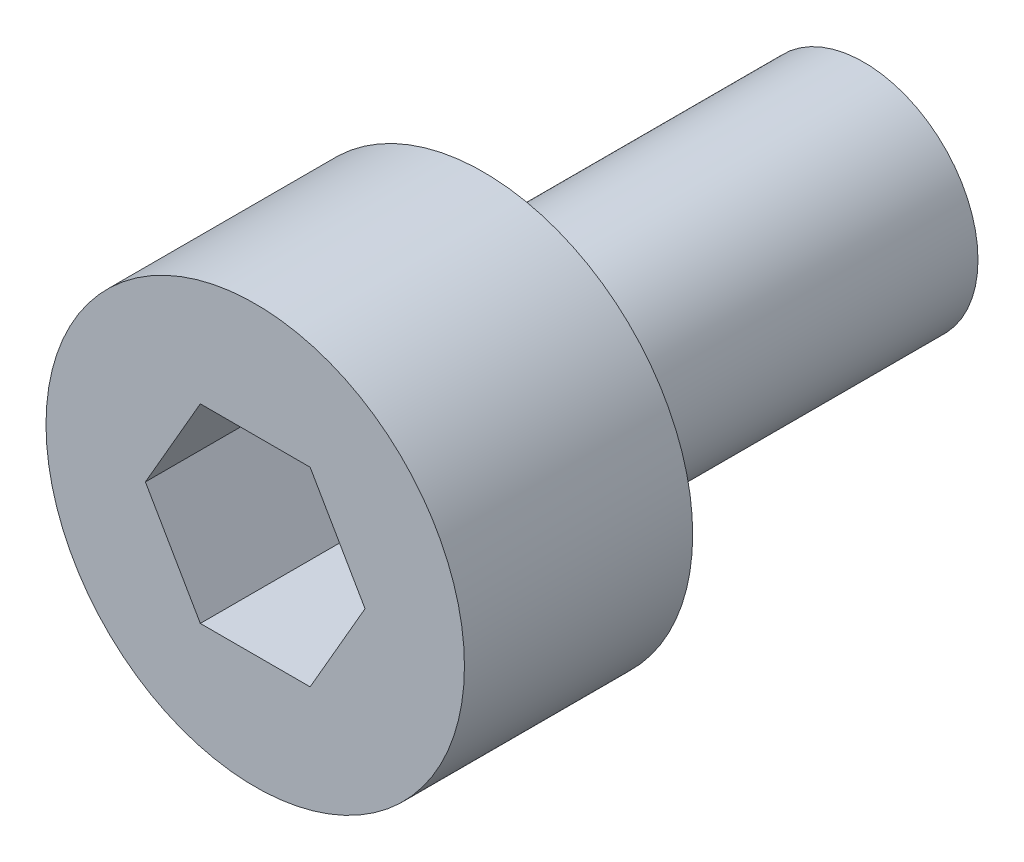
SolidWorks part; units mm, degrees
ref_plane "Plan de face" through (0, 0, 0) normal (0, 0, 1) x (1, 0, 0)
ref_plane "Plan de dessus" through (0, 0, 0) normal (0, 1, 0) x (1, 0, 0)
ref_plane "Plan de droite" through (0, 0, 0) normal (1, 0, 0) x (0, 0, -1)
sketch "Esquisse1" plane through (0, 0, 0) normal (0, 0, 1) x (1, 0, 0)
  circle A0 centre (0, 0) radius 1.5
  dimension "D1" = 3
extrude "Boss.-Extru.1" add sketch "Esquisse1" along normal blind 5
sketch "Esquisse2" plane through (0, 0, 5) normal (0, 0, 1) x (1, 0, 0)
  circle A0 centre (0, 0) radius 2.75
  dimension "D1" = 5.5
extrude "Boss.-Extru.2" add sketch "Esquisse2" along normal blind 3
sketch "Esquisse3" plane through (0, 0, 8) normal (0, 0, 1) x (1, 0, 0)
  line L1 (1.4434, 0) -> (0.7217, 1.25)
  line L2 (0.7217, 1.25) -> (-0.7217, 1.25)
  line L3 (-0.7217, 1.25) -> (-1.4434, 0)
  line L4 (-1.4434, 0) -> (-0.7217, -1.25)
  line L5 (-0.7217, -1.25) -> (0.7217, -1.25)
  line L6 (0.7217, -1.25) -> (1.4434, 0)
  circle A0 centre (0, 0) radius 1.25 construction
  dimension "D1" = 2.5
extrude "Enlèv. mat.-Extru.1" cut sketch "Esquisse3" against normal blind 2
